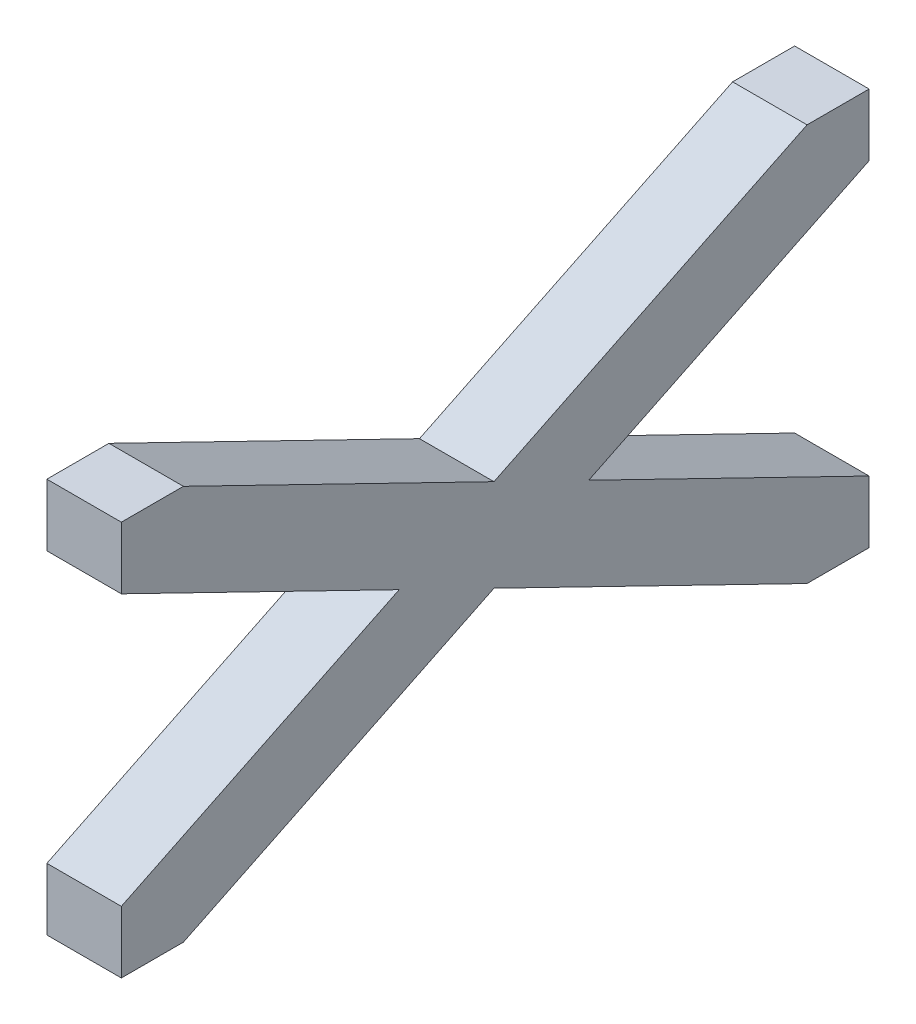
SolidWorks part; units mm, degrees
material "ABS PC"
ref_plane "Front Plane" through (0, 0, 0) normal (0, 0, 1) x (1, 0, 0)
ref_plane "Top Plane" through (0, 0, 0) normal (0, 1, 0) x (1, 0, 0)
ref_plane "Right Plane" through (0, 0, 0) normal (1, 0, 0) x (0, 0, -1)
sketch "Sketch1" plane through (-22.7496, 0, 0) normal (1, 0, 0) x (0, 0, -1)
  line L0 (-112.2272, 51.8367) -> (-105.8772, 51.8367)
  line L1 (-112.2272, 51.8367) -> (-35.7224, 51.8367) construction
  line L2 (-112.2272, 51.8367) -> (-112.2272, 45.4867)
  line L3 (-35.7224, 11.323) -> (-42.0724, 11.323)
  line L4 (-112.2272, 11.323) -> (-35.7224, 11.323) construction
  line L5 (-35.7224, 11.323) -> (-35.7224, 17.673)
  line L6 (-35.7224, 3.703) -> (-35.7224, 17.1251) construction
  line L7 (-35.7224, 17.673) -> (-64.4098, 31.643)
  line L8 (-112.2272, 45.4867) -> (-83.7994, 31.643)
  line L9 (-35.7224, 31.643) -> (-112.2272, 31.643) construction
  line L13 (-35.7224, 51.963) -> (-42.0724, 51.963)
  line L14 (-35.7224, 51.963) -> (-35.7224, 45.613)
  line L15 (-112.2272, 11.4494) -> (-112.2272, 17.7994)
  line L16 (-112.2272, 11.4494) -> (-105.8772, 11.4494)
  line L17 (-35.7224, 45.613) -> (-64.4098, 31.643)
  line L18 (-112.2272, 17.7994) -> (-83.7994, 31.643)
  line L19 (-74.1046, 36.3642) -> (-105.8772, 51.8367)
  line L20 (-74.1046, 26.9219) -> (-105.8772, 11.4494)
  line L21 (-74.1046, 26.9219) -> (-42.0724, 11.323)
  line L22 (-74.1046, 36.3642) -> (-42.0724, 51.963)
  dimension "D1" = 6.35
  dimension "D2" = 6.35
  dimension "D3" = 6.35
  dimension "D4" = 6.35
extrude "Boss-Extrude1" add sketch "Sketch1" against normal blind 7.62
